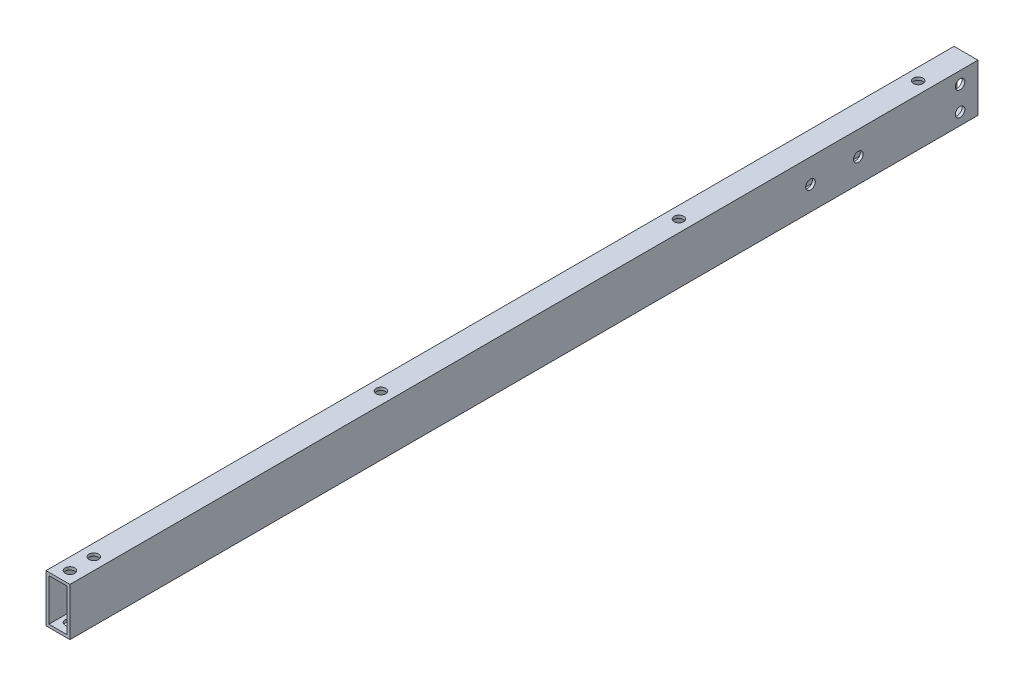
SolidWorks part; units mm, degrees
material "5052-H34"
ref_plane "正面" through (0, 0, 0) normal (0, 0, 1) x (1, 0, 0)
ref_plane "平面" through (0, 0, 0) normal (0, 1, 0) x (1, 0, 0)
ref_plane "右側面" through (0, 0, 0) normal (1, 0, 0) x (0, 0, -1)
sketch "ｽｹｯﾁ1" plane through (0, 0, 0) normal (0, 0, 1) x (1, 0, 0)
  line L1 (-5, 10) -> (5, 10)
  line L2 (-5, 10) -> (-5, -10)
  line L3 (-5, -10) -> (5, -10)
  line L4 (5, 10) -> (5, -10)
  line L5 (-5, 10) -> (5, -10) construction
  line L6 (-5, -10) -> (5, 10) construction
  point P0 (0, 0)
  dimension "D1" = 10
  dimension "D2" = 20
extrude "押し出し-薄板1" add sketch "ｽｹｯﾁ1" along normal blind 379.5 thin
sketch "ｽｹｯﾁ2" plane through (0, 10, 0) normal (0, 1, 0) x (1, 0, 0)
  line L0 (0, -379.5) -> (0, -364.5) construction
  line L1 (5, -379.5) -> (-5, -379.5) construction
  line L2 (-5, -379.5) -> (-5, 0) construction
  line L3 (0, 0) -> (0, -120) construction
  line L4 (5, 0) -> (-5, 0) construction
  circle A0 centre (0, -364.5) radius 2
  circle A1 centre (0, -374.5) radius 2
  circle A2 centre (0, -244.5) radius 2
  circle A3 centre (0, -120) radius 2
  circle A4 centre (0, -20) radius 2
  dimension "D1" = 4
  dimension "D4" = 120
  dimension "D5" = 5
  dimension "D6" = 4
  dimension "D7" = 120
  dimension "D8" = 4
  dimension "D9" = 20
  dimension "D10" = 4
  dimension "D2" = 5
  dimension "D3" = 10
extrude "ｶｯﾄ - 押し出し1" cut sketch "ｽｹｯﾁ2" against normal through all
sketch "ｽｹｯﾁ3" plane through (5, 0, 0) normal (1, 0, 0) x (0, 0, -1)
  line L3 (0, 0) -> (-379.5, 0) construction
  line L4 (-379.5, -10) -> (-379.5, 10) construction
  line L5 (0, -10) -> (0, 10) construction
  circle A0 centre (-7.5, 5) radius 2
  circle A1 centre (-7.5, -5) radius 2
  circle A2 centre (-70, 0) radius 2
  circle A3 centre (-50, 0) radius 2
  dimension "D1" = 10
  dimension "D2" = 4
  dimension "D3" = 7.5
  dimension "D4" = 20
  dimension "D5" = 50
  dimension "D6" = 4
extrude "ｶｯﾄ - 押し出し2" cut sketch "ｽｹｯﾁ3" against normal through all
